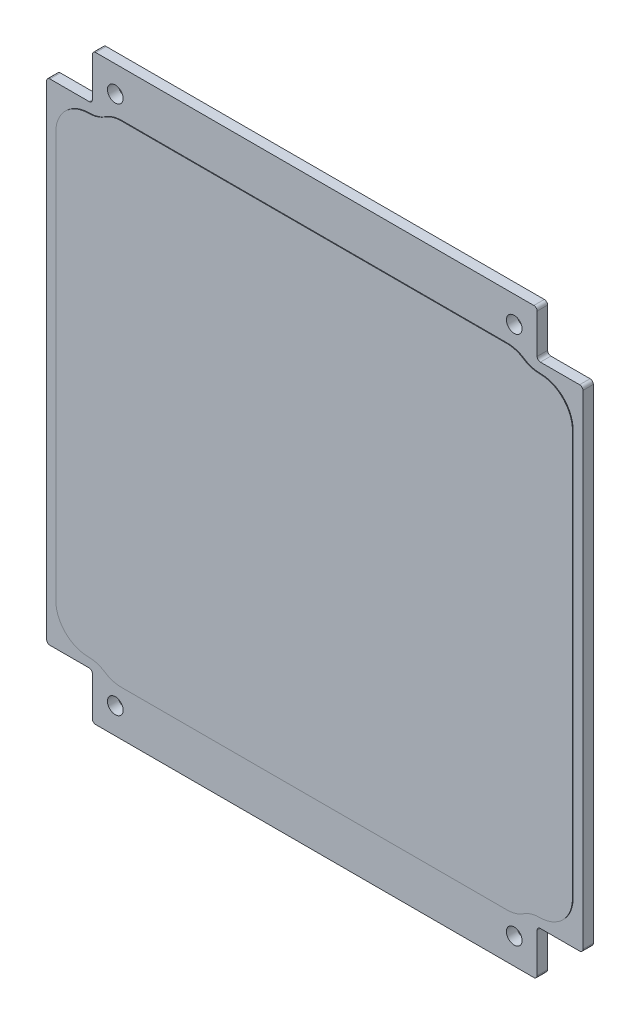
SolidWorks part; units mm, degrees
material "PET"
ref_plane "Front Plane" through (0, 0, 0) normal (0, 0, 1) x (1, 0, 0)
ref_plane "Top Plane" through (0, 0, 0) normal (0, 1, 0) x (1, 0, 0)
ref_plane "Right Plane" through (0, 0, 0) normal (1, 0, 0) x (0, 0, -1)
sketch "Sketch1" plane through (0, 0, 0) normal (0, 0, 1) x (1, 0, 0)
  line L0 (-34, 44) -> (-34, 38)
  line L1 (-33.5, -44.5) -> (33.5, -44.5)
  line L2 (-41, 37) -> (-41, -37)
  line L3 (-33.5, 44.5) -> (33.5, 44.5)
  line L4 (41, -37) -> (41, 37)
  line L5 (34, -44) -> (34, -38)
  line L6 (34.5, -37.5) -> (40.5, -37.5)
  line L7 (-34.5, 37.5) -> (-40.5, 37.5)
  line L8 (34, 44) -> (34, 38)
  line L9 (34.5, 37.5) -> (40.5, 37.5)
  line L10 (-40.5, -37.5) -> (-34.5, -37.5)
  line L11 (-34, -38) -> (-34, -44)
  line L12 (-34.5, -38) -> (34.5, 38) construction
  line L13 (34.5, -38) -> (-34.5, 38) construction
  arc A0 (-33.5, 44.5) -> (-34, 44) centre (-33.5, 44) ccw
  arc A1 (33.5, 44.5) -> (34, 44) centre (33.5, 44) cw
  arc A2 (34, 38) -> (34.5, 37.5) centre (34.5, 38) ccw
  arc A3 (40.5, 37.5) -> (41, 37) centre (40.5, 37) cw
  arc A4 (33.5, -44.5) -> (34, -44) centre (33.5, -44) ccw
  arc A5 (34.5, -37.5) -> (34, -38) centre (34.5, -38) ccw
  arc A6 (40.5, -37.5) -> (41, -37) centre (40.5, -37) ccw
  arc A7 (-34, -44) -> (-33.5, -44.5) centre (-33.5, -44) ccw
  arc A8 (-34, -38) -> (-34.5, -37.5) centre (-34.5, -38) ccw
  arc A9 (-41, -37) -> (-40.5, -37.5) centre (-40.5, -37) ccw
  arc A10 (-40.5, 37.5) -> (-41, 37) centre (-40.5, 37) ccw
  arc A11 (-34.5, 37.5) -> (-34, 38) centre (-34.5, 38) ccw
  point P0 (0, 0)
  dimension "D4" = 0.5
  dimension "D1" = 7
  dimension "D2" = 7
  dimension "D3" = 7
  dimension "D5" = 7
  dimension "D6" = 7
  dimension "D7" = 7
  dimension "D8" = 7
  dimension "D9" = 7
  dimension "D10" = 89
  dimension "D11" = 82
extrude "Boss-Extrude1" add sketch "Sketch1" along normal blind 1.6
sketch "Esboço1" plane through (0, 0, 1.6) normal (0, 0, 1) x (1, 0, 0)
  line L0 (-29.5, 0) -> (21.969, 0) construction
  line L1 (-29.5, -37.5) -> (29.5, -37.5)
  line L2 (0, 0) -> (0, -21.9481) construction
  line L3 (-29.5, 37.5) -> (29.5, 37.5)
  line L5 (-29.5, -32.5) -> (29.5, 32.5) construction
  line L6 (-29.5, 32.5) -> (29.5, -32.5) construction
  line L11 (39.5, -31) -> (39.5, 31)
  line L13 (-39.5, -31) -> (-39.5, 31)
  line L14 (39.5, -36) -> (-39.5, 36) construction
  line L15 (39.5, 36) -> (-39.5, -36) construction
  arc A0 (-29.5, 37.5) -> (-32, 36.75) centre (-29.5, 32.9583) ccw
  arc A1 (-29.5, -37.5) -> (-32, -36.75) centre (-29.5, -32.9583) cw
  arc A2 (-34.5, -36) -> (-32, -36.75) centre (-34.5, -40.5417) cw
  arc A3 (29.5, -37.5) -> (32, -36.75) centre (29.5, -32.9583) ccw
  arc A4 (39.5, 31) -> (34.5, 36) centre (34.5, 31) ccw
  arc A5 (34.5, -36) -> (39.5, -31) centre (34.5, -31) ccw
  arc A6 (-34.5, -36) -> (-39.5, -31) centre (-34.5, -31) cw
  arc A7 (-34.5, 36) -> (-39.5, 31) centre (-34.5, 31) ccw
  arc A8 (-34.5, 36) -> (-32, 36.75) centre (-34.5, 40.5417) ccw
  arc A9 (34.5, -36) -> (32, -36.75) centre (34.5, -40.5417) ccw
  arc A10 (34.5, 36) -> (32, 36.75) centre (34.5, 40.5417) cw
  arc A11 (29.5, 37.5) -> (32, 36.75) centre (29.5, 32.9583) cw
  point P0 (0, 0)
  point P15 (0, 0)
  dimension "D6" = 5
  dimension "D3" = 75
  dimension "D4" = 79
extrude "Boss-Extrude2" add sketch "Esboço1" along normal blind 0.1
hole_wizard "M2 Hole1-FixingStructure" positions "Sketch3" profile "Sketch2" hole size "M2" standard "DIN"
sketch "Sketch3" plane through (0, 0, 0) normal (0, 0, -1) x (-1, 0, 0)
  line L0 (-33.5, 44.5) -> (33.5, 44.5) construction
  line L1 (33.5, -44.5) -> (-33.5, -44.5) construction
  line L2 (-41, -37) -> (-41, 37) construction
  line L3 (41, 37) -> (41, -37) construction
  point P0 (-30.5, 40.5)
  point P2 (30.5, 40.5)
  point P4 (-30.5, -40.5)
  point P6 (30.5, -40.5)
  dimension "D1" = 4
  dimension "D2" = 4
  dimension "D3" = 10.5
  dimension "D4" = 10.5
sketch "Sketch2" plane through (30.5, 40.5, 0) normal (1, 0, 0) x (0, 1, 0)
  line L0 (0, 0) -> (0, 200.721)
  line L1 (0, 200.721) -> (1.2, 200)
  line L2 (1.2, 200) -> (1.2, 0)
  line L5 (1.2, 0) -> (0, 0)
  line L10 (0, 200.721) -> (-1.2, 200) construction
  line L11 (0, -6.35) -> (0, 107.95) construction
  dimension "Hole Dia." = 2.4
  dimension "Hole Depth" = 200
  dimension "Drill Angle" = 118
